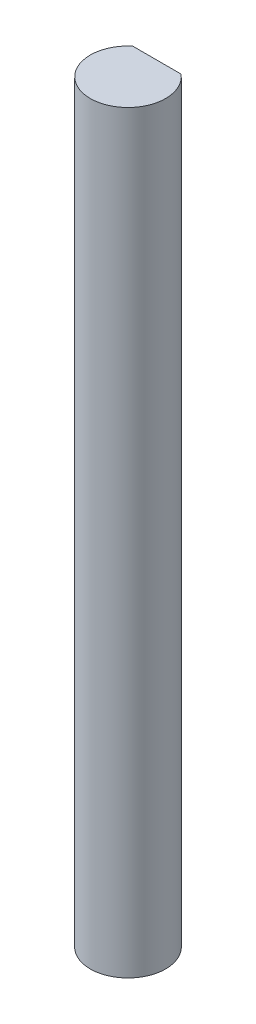
SolidWorks part; units mm, degrees
material "1023 Листовая углеродистая сталь (SS)"
ref_plane "Спереди" through (0, 0, 0) normal (0, 0, 1) x (1, 0, 0)
ref_plane "Сверху" through (0, 0, 0) normal (0, 1, 0) x (1, 0, 0)
ref_plane "Справа" through (0, 0, 0) normal (1, 0, 0) x (0, 0, -1)
sketch "Эскиз1" plane through (0, 0, 0) normal (0, 1, 0) x (1, 0, 0)
  circle A0 centre (0, 0) radius 3
  dimension "D1" = 6
extrude "Бобышка-Вытянуть1" add sketch "Эскиз1" along normal blind 60
sketch "Эскиз2" plane through (0, 60, 0) normal (0, 1, 0) x (1, 0, 0)
  line L1 (-2.5, 4.3) -> (2.5, 4.3)
  line L2 (-2.5, 4.3) -> (-2.5, 2.3)
  line L3 (-2.5, 2.3) -> (2.5, 2.3)
  line L4 (2.5, 4.3) -> (2.5, 2.3)
  line L5 (-2.5, 4.3) -> (2.5, 2.3) construction
  line L6 (-2.5, 2.3) -> (2.5, 4.3) construction
  point P0 (0, 3.3)
  dimension "D1" = 2.3
  dimension "D2" = 2
  dimension "D3" = 5
extrude "Вырез-Вытянуть1" cut sketch "Эскиз2" against normal through all
